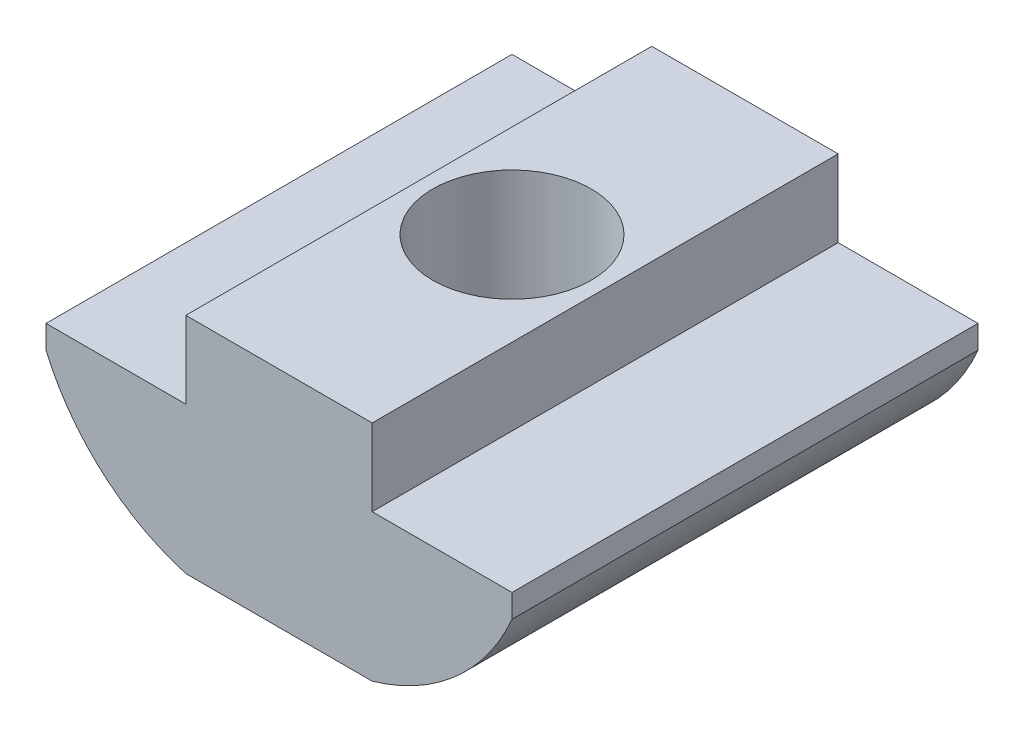
SolidWorks part; units mm, degrees
ref_plane "前视基准面" through (0, 0, 0) normal (0, 0, 1) x (1, 0, 0)
ref_plane "上视基准面" through (0, 0, 0) normal (0, 1, 0) x (1, 0, 0)
ref_plane "右视基准面" through (0, 0, 0) normal (1, 0, 0) x (0, 0, -1)
sketch "草图1" plane through (0, 0, 0) normal (0, 0, 1) x (1, 0, 0)
  line B0 (4, -9.6) -> (-4, -9.6)
  line B1 (10, -3.3) -> (10, -4.3)
  line B2 (10, -3.3) -> (4, -3.3)
  line B3 (-4, -3.3) -> (-10, -3.3)
  line B4 (-10, -3.3) -> (-10, -4.3)
  line B5 (4, -3.3) -> (4, 0)
  line B6 (-4, -3.3) -> (-4, 0)
  line B7 (4, 0) -> (-4, 0)
  arc B8 (4, -9.6) -> (10, -4.3) centre (1.3752, -0.5823) ccw
  arc B9 (-10, -4.3) -> (-4, -9.6) centre (-1.3752, -0.5823) ccw
sketch_block_instance "A$C509E76BE-1"
sketch_block "A$C509E76BE"
extrude "凸台-拉伸1" add sketch "草图1" along normal mid plane 20
sketch "草图3" plane through (0, 0, 0) normal (0, 1, 0) x (1, 0, 0)
  point P0 (0, 0)
hole_wizard "M8 螺纹孔1" positions "3D草图2" profile "草图5" tap size "M8" standard "Iso"
sketch3d "3D草图2"
  point P0 (0, 0, 0)
sketch "草图5" plane through (0, 0, 0) normal (1, 0, 0) x (0, 0, 1)
  line L0 (0, 0) -> (0, 21.7929)
  line L1 (0, 21.7929) -> (3.4, 19.75)
  line L2 (3.4, 19.75) -> (3.4, 0)
  line L5 (3.4, 0) -> (0, 0)
  line L10 (0, 21.7929) -> (-3.4, 19.75) construction
  line L11 (0, -6.35) -> (0, 107.95) construction
  dimension "螺纹孔钻头直径" = 6.8
  dimension "螺纹孔钻头深度" = 19.75
  dimension "导头角度" = 118
cosmetic thread "孔螺蚊线1"
